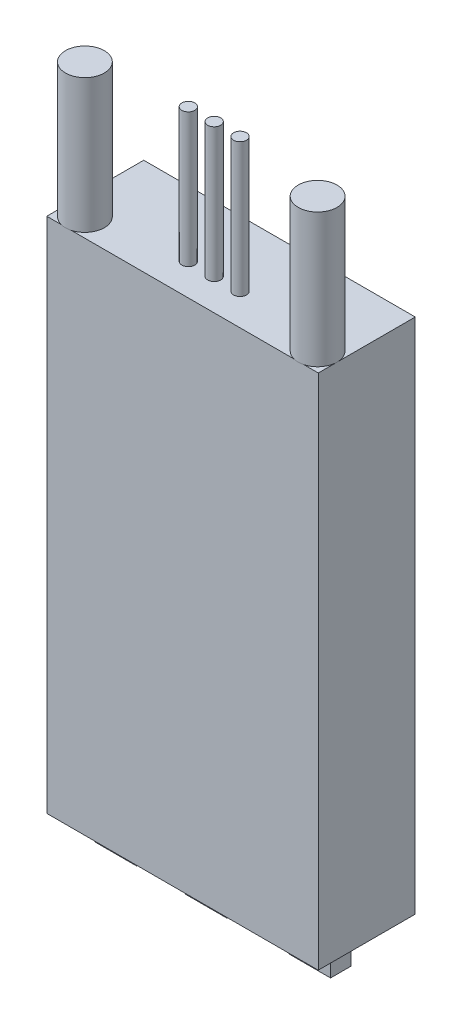
SolidWorks part; units mm, degrees
ref_plane "Front Plane" through (0, 0, 0) normal (1, 0, 0) x (0, 1, 0)
ref_plane "Top Plane" through (0, 0, 0) normal (0, 0, 1) x (0, 1, 0)
ref_plane "Right Plane" through (0, 0, 0) normal (0, 1, 0) x (-1, 0, 0)
sketch "Sketch1" plane through (0, 0, 0) normal (0, 0, 1) x (0, 1, 0)
  line L1 (-20, 10.5) -> (20, 10.5)
  line L2 (-20, 10.5) -> (-20, -10.5)
  line L3 (-20, -10.5) -> (20, -10.5)
  line L4 (20, 10.5) -> (20, -10.5)
  line L5 (-20, 10.5) -> (20, -10.5) construction
  line L6 (-20, -10.5) -> (20, 10.5) construction
  point P0 (0, 0)
  dimension "D1" = 40
  dimension "D2" = 21
extrude "Boss-Extrude1" add sketch "Sketch1" along normal mid plane 7.5
sketch "Sketch2" plane through (0, 0, 0) normal (0, 0, 1) x (0, 1, 0)
  line L0 (-20, 10.5) -> (-20, -10.5) construction
  line L1 (-20, 9.7) -> (-23, 9.7)
  line L2 (-20, 9.7) -> (-20, 6.5)
  line L3 (-20, 6.5) -> (-23, 6.5)
  line L4 (-23, 9.7) -> (-23, 6.5)
  line L5 (-20, -10.5) -> (20, -10.5) construction
  line L6 (-20, 2.7) -> (-23, 2.7)
  line L7 (-20, 2.7) -> (-20, -0.5)
  line L8 (-20, -0.5) -> (-23, -0.5)
  line L9 (-23, 2.7) -> (-23, -0.5)
  line L10 (-20, -5.3) -> (-23, -5.3)
  line L11 (-20, -5.3) -> (-20, -8.5)
  line L12 (-20, -8.5) -> (-23, -8.5)
  line L13 (-23, -5.3) -> (-23, -8.5)
  line L16 (20, -10.5) -> (20, 10.5) construction
  point P20 (-21.5, -8.5)
  dimension "D1" = 17
  dimension "D2" = 3.2
  dimension "D3" = 43
  dimension "D4" = 2
  dimension "D5" = 10
extrude "Boss-Extrude2" add sketch "Sketch2" along normal mid plane 1.6
sketch "Sketch3" plane through (0, 20, 0) normal (0, 1, 0) x (-1, 0, 0)
  line L0 (-10.5, 0) -> (10.5, 0) construction
  line L1 (-10.5, 3.75) -> (-10.5, -3.75) construction
  line L2 (10.5, 3.75) -> (10.5, -3.75) construction
  line L3 (-10.5, 0.8) -> (10.5, 0.8) construction
  circle A0 centre (-9, 2.3) radius 1.5
  circle A1 centre (9, 2.3) radius 1.5
  circle A2 centre (0, 1.3) radius 0.5
  circle A3 centre (2, 1.3) radius 0.5
  circle A4 centre (-2, 1.3) radius 0.5
  dimension "D2" = 3
  dimension "D3" = 1
  dimension "D1" = 0.8
  dimension "D4" = 2
  dimension "D5" = 2
extrude "Boss-Extrude3" add sketch "Sketch3" along normal blind 10.3667
